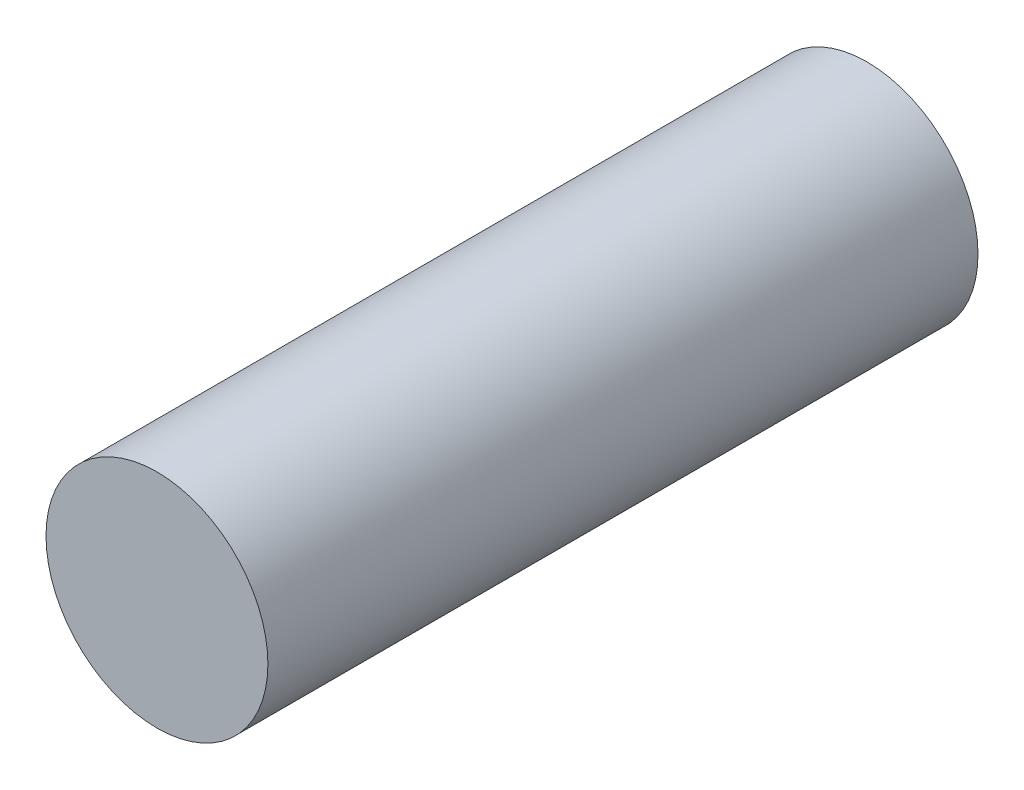
SolidWorks part; units mm, degrees
ref_plane "Plan de face" through (0, 0, 0) normal (0, 0, 1) x (1, 0, 0)
ref_plane "Plan de dessus" through (0, 0, 0) normal (0, 1, 0) x (1, 0, 0)
ref_plane "Plan de droite" through (0, 0, 0) normal (1, 0, 0) x (0, 0, -1)
sketch "Esquisse1" plane through (0, 0, 0) normal (0, 0, 1) x (1, 0, 0)
  circle A0 centre (0, 0) radius 12.5
  dimension "D1" = 25
extrude "Boss.-Extru.1" add sketch "Esquisse1" along normal blind 80
